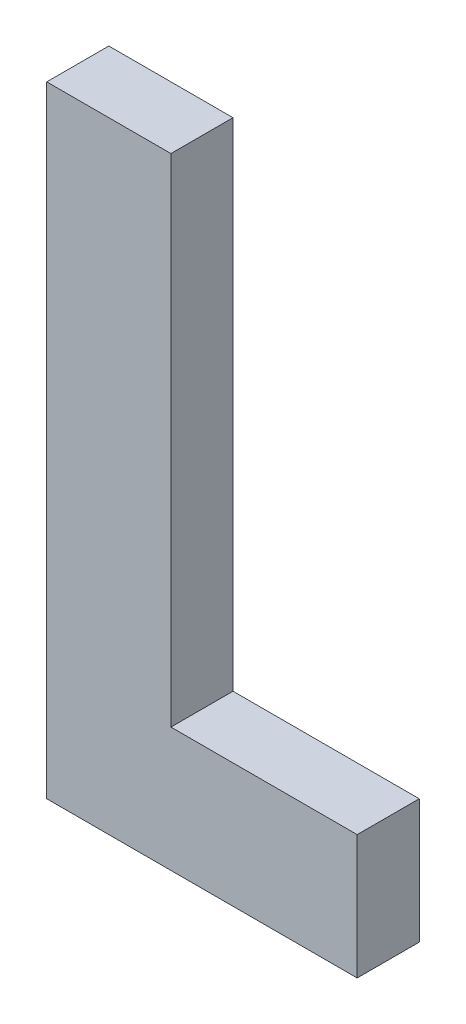
SolidWorks part; units mm, degrees
ref_plane "Front Plane" through (0, 0, 0) normal (0, 0, 1) x (1, 0, 0)
ref_plane "Top Plane" through (0, 0, 0) normal (0, 1, 0) x (1, 0, 0)
ref_plane "Right Plane" through (0, 0, 0) normal (1, 0, 0) x (0, 0, -1)
sketch "Sketch2" plane through (0, 0, 0) normal (0, 0, 1) x (1, 0, 0)
  line L1 (0, 0) -> (20, 0)
  line L2 (0, 0) -> (0, -80)
  line L4 (20, 0) -> (20, -80)
  line L5 (20, -80) -> (50, -80)
  line L6 (0, -80) -> (0, -100)
  line L7 (0, -100) -> (50, -100)
  line L8 (50, -80) -> (50, -100)
extrude "Boss-Extrude1" add sketch "Sketch2" along normal blind 10
